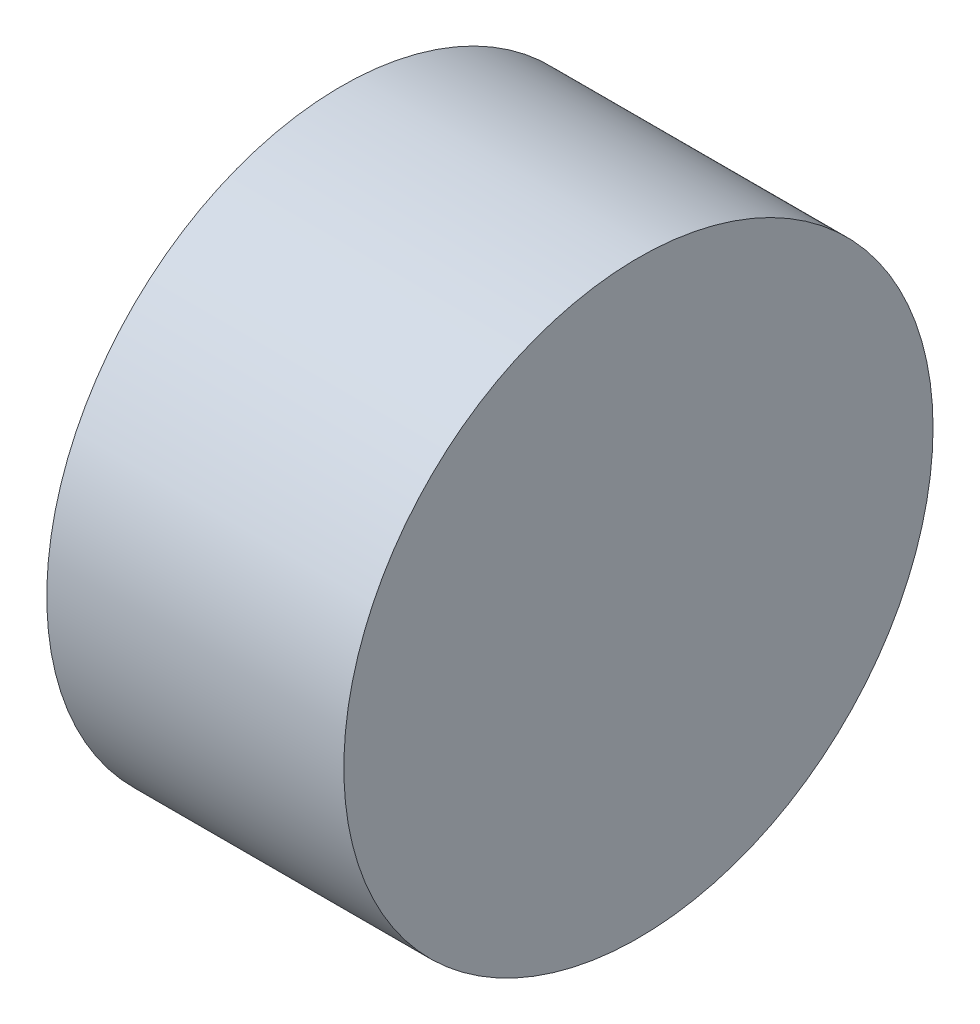
SolidWorks part; units mm, degrees
ref_plane "Front Plane" through (0, 0, 0) normal (0, 0, 1) x (1, 0, 0)
ref_plane "Top Plane" through (0, 0, 0) normal (0, 1, 0) x (1, 0, 0)
ref_plane "Right Plane" through (0, 0, 0) normal (1, 0, 0) x (0, 0, -1)
sketch "Sketch5" plane through (0, 0, 0) normal (0, 1, 0) x (1, 0, 0)
  line L0 (150.7, 0) -> (150.7, -8.8)
  line L1 (-55, 0) -> (55, 0) construction
  line L2 (150.7, -8.8) -> (143, -10.9)
  line L3 (143, -10.9) -> (143, -12)
  line L4 (143, -12) -> (155.1, -12)
  line L5 (155.1, -12) -> (155.1, 0)
  line L6 (155.1, 0) -> (150.7, 0)
  dimension "D1" = 12
  dimension "D2" = 8.8
  dimension "D3" = 1.1
  dimension "D4" = 4.4
  dimension "D5" = 12.1
  dimension "D6" = 150.7
revolve "Revolve1" add sketch "Sketch5" angle 360 about L6
